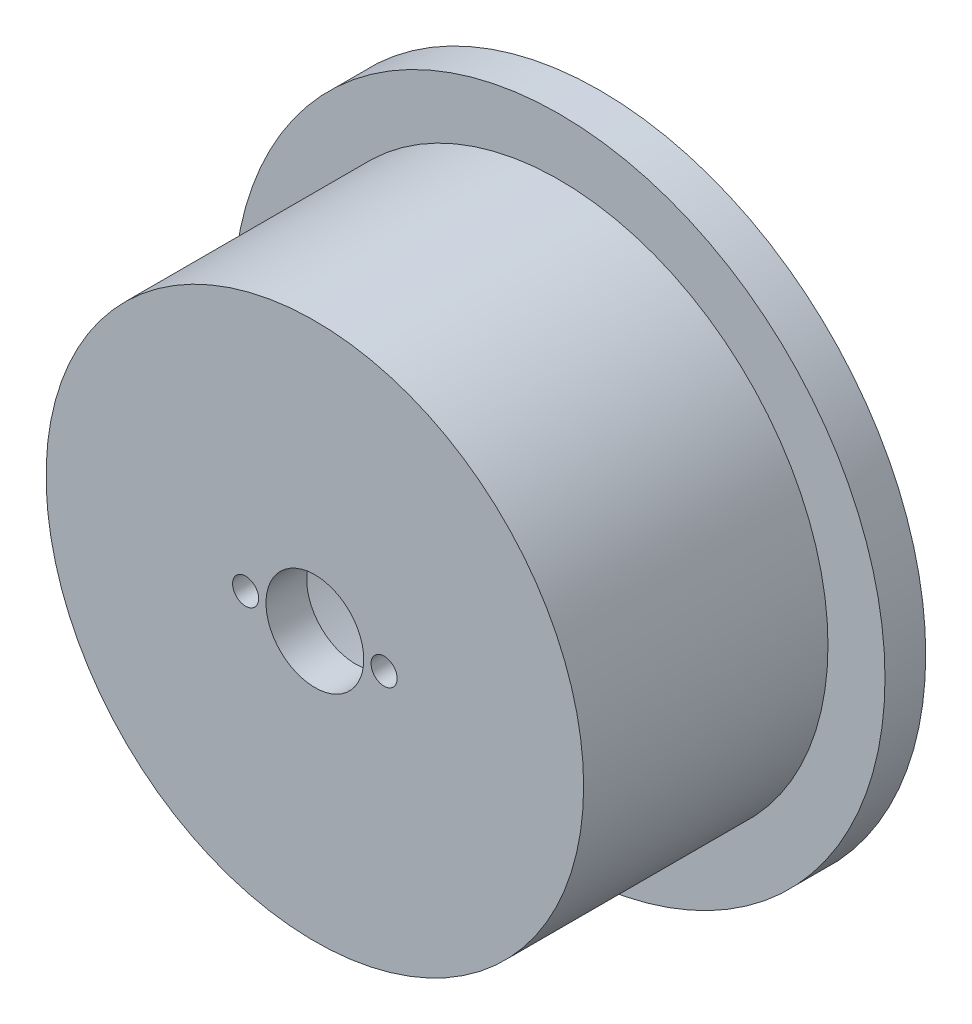
SolidWorks part; units mm, degrees
ref_plane "Front Plane" through (0, 0, 0) normal (0, 0, 1) x (1, 0, 0)
ref_plane "Top Plane" through (0, 0, 0) normal (0, 1, 0) x (1, 0, 0)
ref_plane "Right Plane" through (0, 0, 0) normal (1, 0, 0) x (0, 0, -1)
sketch "Sketch1" plane through (0, 0, 0) normal (0, 0, 1) x (1, 0, 0)
  circle A0 centre (0, 0) radius 40
  circle A1 centre (0, 0) radius 28
extrude "Flange" add sketch "Sketch1" along normal blind 5
ref_plane "Plane_z5" through (0, 0, 5) normal (0, 0, 1) x (1, 0, 0)
sketch "Sketch2" plane through (0, 0, 5) normal (0, 0, 1) x (1, 0, 0)
  circle A0 centre (0, 0) radius 33
  circle A1 centre (0, 0) radius 28
extrude "Tube" add sketch "Sketch2" along normal blind 25
ref_plane "Plane_z30" through (0, 0, 30) normal (0, 0, 1) x (1, 0, 0)
sketch "Sketch3" plane through (0, 0, 30) normal (0, 0, 1) x (1, 0, 0)
  circle A0 centre (0, 0) radius 33
extrude "Plate" add sketch "Sketch3" along normal blind 5
sketch "Sketch4" plane through (0, 0, 30) normal (0, 0, 1) x (1, 0, 0)
  circle A0 centre (0, 0) radius 6
extrude "Shaft_hole" cut sketch "Sketch4" along normal blind 5
sketch "Sketch5" plane through (0, 0, 30) normal (0, 0, 1) x (1, 0, 0)
  circle A0 centre (-8.5, 0) radius 1.6
  circle A1 centre (8.5, 0) radius 1.6
extrude "Motor_screws" cut sketch "Sketch5" along normal blind 5
sketch "Sketch6" plane through (0, 0, 0) normal (0, 0, 1) x (1, 0, 0)
  circle A0 centre (21.2132, 21.2132) radius 1.7
  circle A1 centre (-21.2132, 21.2132) radius 1.7
  circle A2 centre (-21.2132, -21.2132) radius 1.7
  circle A3 centre (21.2132, -21.2132) radius 1.7
extrude "Grommet_holes" cut sketch "Sketch6" along normal blind 5
